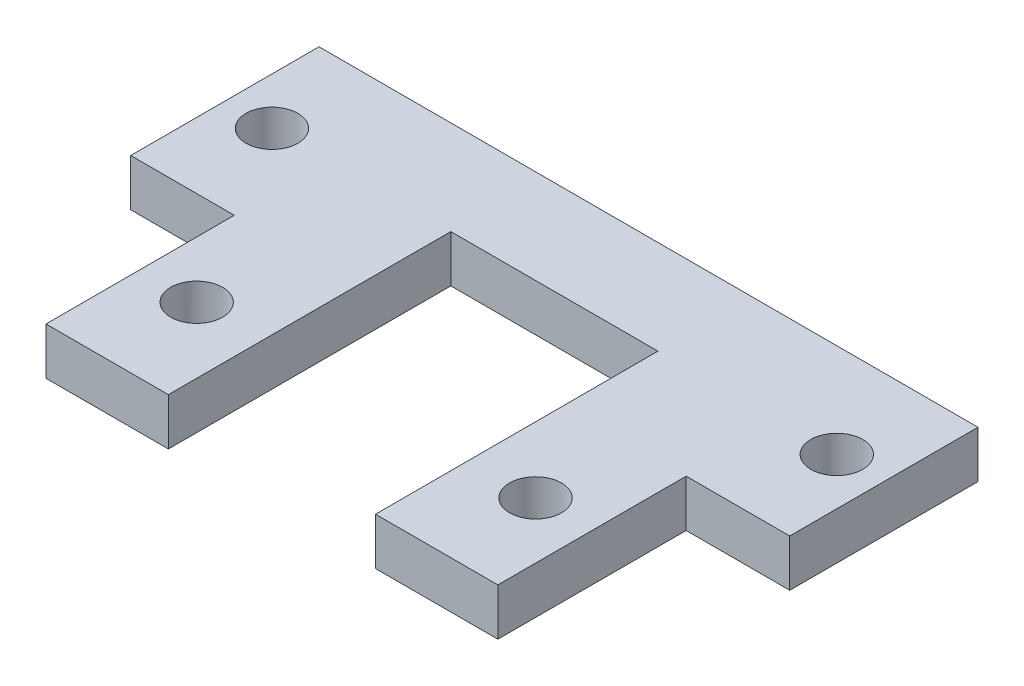
SolidWorks part; units mm, degrees
ref_plane "Front Plane" through (0, 0, 0) normal (1, 0, 0) x (0, 1, 0)
ref_plane "Top Plane" through (0, 0, 0) normal (0, 0, 1) x (0, 1, 0)
ref_plane "Right Plane" through (0, 0, 0) normal (0, 1, 0) x (-1, 0, 0)
sketch "Sketch1" plane through (0, 0, 0) normal (0, 1, 0) x (-1, 0, 0)
  line L1 (19.05, -6.35) -> (-19.05, -6.35) construction
  line L2 (19.05, -6.35) -> (19.05, 6.35) construction
  line L3 (19.05, 6.35) -> (-19.05, 6.35) construction
  line L4 (-19.05, -6.35) -> (-19.05, 6.35) construction
  line L5 (19.05, -6.35) -> (-19.05, 6.35) construction
  line L6 (19.05, 6.35) -> (-19.05, -6.35) construction
  line L7 (7.9375, -6.35) -> (-7.9375, -6.35) construction
  line L8 (7.9375, -6.35) -> (7.9375, 6.35) construction
  line L9 (7.9375, 6.35) -> (-7.9375, 6.35) construction
  line L10 (-7.9375, -6.35) -> (-7.9375, 6.35) construction
  line L11 (7.9375, -6.35) -> (-7.9375, 6.35) construction
  line L12 (7.9375, 6.35) -> (-7.9375, -6.35) construction
  line L13 (22.225, -6.35) -> (-22.225, -6.35)
  line L14 (22.225, -6.35) -> (22.225, 6.35)
  line L15 (22.225, 6.35) -> (-22.225, 6.35)
  line L16 (-22.225, -6.35) -> (-22.225, 6.35)
  line L17 (22.225, -6.35) -> (-22.225, 6.35) construction
  line L18 (22.225, 6.35) -> (-22.225, -6.35) construction
  line L19 (12.7, -3.175) -> (-12.7, -3.175) construction
  line L20 (12.7, -3.175) -> (12.7, 3.175) construction
  line L21 (12.7, 3.175) -> (-12.7, 3.175) construction
  line L22 (-12.7, -3.175) -> (-12.7, 3.175) construction
  line L23 (12.7, -3.175) -> (-12.7, 3.175) construction
  line L24 (12.7, 3.175) -> (-12.7, -3.175) construction
  line L25 (-15.24, 6.35) -> (15.24, 6.35)
  line L26 (-15.24, 6.35) -> (-15.24, 19.05)
  line L27 (-15.24, 19.05) -> (15.24, 19.05)
  line L28 (15.24, 6.35) -> (15.24, 19.05)
  circle A1 centre (19.05, 0) radius 1.75
  circle A2 centre (-19.05, 0) radius 1.75
  circle A5 centre (19.05, 0) radius 9.017 construction
  point P0 (0, 0)
  point P8 (0, 0)
  point P15 (0, 0)
  point P20 (0, 0)
  point P35 (0, 19.05)
  point P36 (0, 19.05)
  dimension "D3" = 3.5
  dimension "D8" = 18.034
  dimension "D1" = 38.1
  dimension "D2" = 12.7
  dimension "D4" = 15.875
  dimension "D5" = 25.4
  dimension "D6" = 6.35
  dimension "D7" = 44.45
  dimension "D9" = 30.48
  dimension "D11" = 12.7
extrude "Boss-Extrude1" add sketch "Sketch1" along normal blind 3.175
sketch "Sketch2" plane through (0, 3.175, 0) normal (0, 1, 0) x (-1, 0, 0)
  line L1 (19.05, -19.05) -> (-19.05, -19.05) construction
  line L2 (19.05, -19.05) -> (19.05, 19.05) construction
  line L3 (19.05, 19.05) -> (-19.05, 19.05) construction
  line L4 (-19.05, -19.05) -> (-19.05, 19.05) construction
  line L5 (19.05, -19.05) -> (-19.05, 19.05) construction
  line L6 (19.05, 19.05) -> (-19.05, -19.05) construction
  line L7 (-6.985, 19.05) -> (6.985, 19.05) construction
  line L8 (-6.985, 19.05) -> (-6.985, 6.35) construction
  line L9 (-6.985, 6.35) -> (6.985, 6.35) construction
  line L10 (6.985, 19.05) -> (6.985, 6.35) construction
  line L11 (-15.24, 6.35) -> (-22.225, 6.35) construction
  line L12 (-15.875, 19.05) -> (-15.875, 6.35) construction
  line L13 (-15.875, 6.35) -> (-6.985, 6.35) construction
  line L14 (0, 6.35) -> (0, 0) construction
  circle A0 centre (-11.43, 12.7) radius 1.75
  circle A1 centre (11.43, 12.7) radius 1.75
  point P0 (0, 0)
  point P13 (0, 6.35)
  point P14 (-11.43, 6.35)
  dimension "D5" = 3.5
  dimension "D1" = 38.1
  dimension "D2" = 8.89
  dimension "D3" = 3.175
  dimension "D4" = 6.35
extrude "Cut-Extrude1" cut sketch "Sketch2" against normal blind 12.192
sketch "Sketch3" plane through (0, 3.175, 0) normal (0, 1, 0) x (-1, 0, 0)
  line L0 (-15.24, 19.05) -> (15.24, 19.05) construction
  line L1 (-6.985, 19.05) -> (6.985, 19.05)
  line L2 (-6.985, 19.05) -> (-6.985, 0)
  line L3 (-6.985, 0) -> (6.985, 0)
  line L4 (6.985, 19.05) -> (6.985, 0)
  point P6 (0, 0)
  point P7 (0, 0)
  dimension "D1" = 13.97
  dimension "D2" = 19.05
extrude "Cut-Extrude2" cut sketch "Sketch3" against normal blind 25.4
